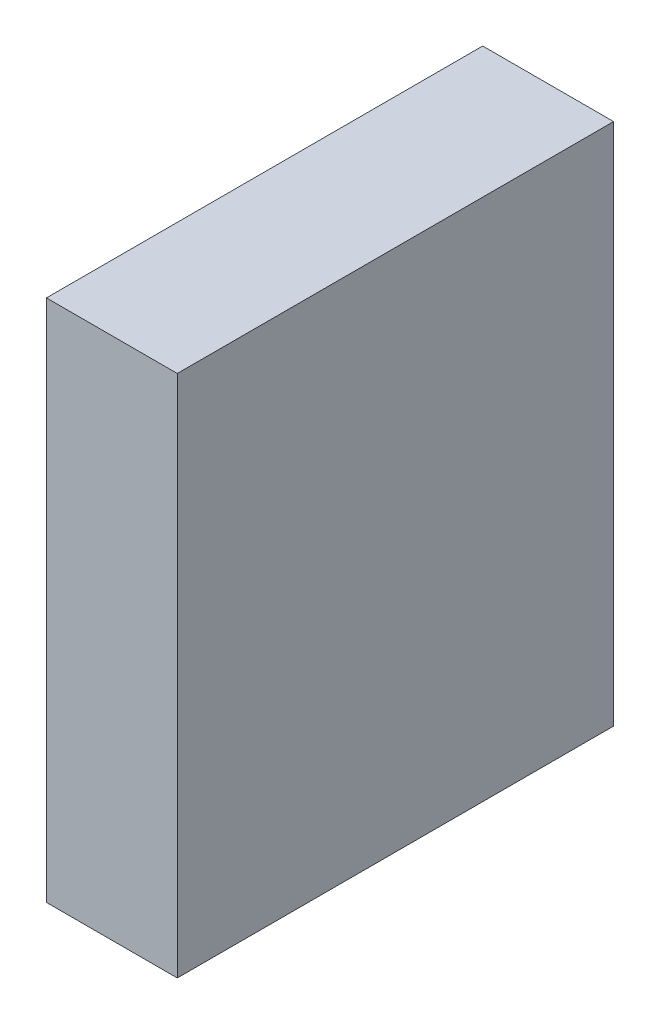
SolidWorks part; units mm, degrees
ref_plane "Front Plane" through (0, 0, 0) normal (0, 0, 1) x (1, 0, 0)
ref_plane "Top Plane" through (0, 0, 0) normal (0, 1, 0) x (1, 0, 0)
ref_plane "Right Plane" through (0, 0, 0) normal (1, 0, 0) x (0, 0, -1)
sketch "Sketch1" plane through (0, 0, 0) normal (0, 0, 1) x (1, 0, 0)
  line L1 (-1.2722, -8.1361) -> (1.7278, -8.1361)
  line L2 (-1.2722, -8.1361) -> (-1.2722, 3.8639)
  line L3 (-1.2722, 3.8639) -> (1.7278, 3.8639)
  line L4 (1.7278, -8.1361) -> (1.7278, 3.8639)
  line L5 (-1.2722, -8.1361) -> (1.7278, 3.8639) construction
  line L6 (-1.2722, 3.8639) -> (1.7278, -8.1361) construction
  dimension "D1" = 3
  dimension "D2" = 12
extrude "Boss-Extrude2" add sketch "Sketch1" along normal blind 10
